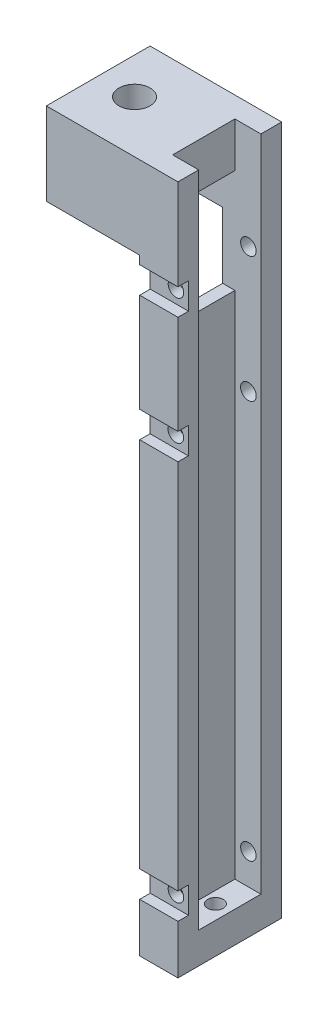
SolidWorks part; units mm, degrees
material "Delrin 2700 NC010, Low Viscosity Acetal Copolymer (SS)"
ref_plane "Front Plane" through (0, 0, 0) normal (0, 0, 1) x (1, 0, 0)
ref_plane "Top Plane" through (0, 0, 0) normal (0, 1, 0) x (1, 0, 0)
ref_plane "Right Plane" through (0, 0, 0) normal (1, 0, 0) x (0, 0, -1)
sketch "Sketch1" plane through (0, 0, 0) normal (0, 0, 1) x (1, 0, 0)
  line L0 (-4, 0) -> (-0.82, 0)
  line L1 (-0.82, 0) -> (-0.82, 21.5)
  line L2 (-6.32, 21.5) -> (-6.32, 17.5)
  line L3 (-4, 17.5) -> (-4, 0)
  line L4 (-6.32, 17.5) -> (-4, 17.5)
  line L5 (-0.82, 21.5) -> (-6.32, 21.5)
  dimension "D1" = 3.18
  dimension "D2" = 5.5
  dimension "D3" = 4
extrude "Boss-Extrude2" add sketch "Sketch1" along normal blind 10
sketch "Sketch2" plane through (-0.82, 0, 0) normal (1, 0, 0) x (0, 0, -1)
  line L1 (-10, 0) -> (0, 0) construction
  line L3 (-8, 0) -> (-2, 0)
  line L4 (-2, 0) -> (-2, 21.5)
  line L5 (-10, 21.5) -> (0, 21.5) construction
  line L6 (-2, 21.5) -> (-8, 21.5)
  line L7 (-8, 21.5) -> (-8, 0)
extrude "Cut-Extrude1" cut sketch "Sketch2" against normal blind 2
sketch "Sketch18" plane through (-6.32, 0, 0) normal (-1, 0, 0) x (0, 0, 1)
  line L0 (0, 21.5) -> (0, 17.5)
  line L1 (0, 21.5) -> (10, 21.5)
  line L2 (10, 21.5) -> (10, 17.5)
  line L3 (10, 17.5) -> (0, 17.5)
extrude "Cut-Extrude6" cut sketch "Sketch18" against normal blind 2.32
sketch "Sketch19" plane through (0, 21.5, 0) normal (0, 1, 0) x (1, 0, 0)
  line L0 (-0.82, -10) -> (-4, -10)
  line L1 (-4, -10) -> (-4, 0)
  line L2 (-4, 0) -> (-0.82, 0)
  line L3 (-0.82, 0) -> (-0.82, -2)
  line L4 (-0.82, -2) -> (-2.82, -2)
  line L5 (-2.82, -2) -> (-2.82, -8)
  line L6 (-2.82, -8) -> (-0.82, -8)
  line L7 (-0.82, -8) -> (-0.82, -10)
extrude "Boss-Extrude4" add sketch "Sketch19" along normal blind 35.965
sketch "Sketch20" plane through (-4, 0, 0) normal (-1, 0, 0) x (0, 0, 1)
  line L0 (10, 57.465) -> (10, 53.147)
  line L1 (10, 57.465) -> (10, 0) construction
  line L2 (10, 53.147) -> (0, 53.147)
  line L3 (0, 57.465) -> (0, 0) construction
  line L4 (0, 53.147) -> (0, 57.465)
  line L5 (0, 57.465) -> (10, 57.465)
  dimension "D1" = 4.318
extrude "Boss-Extrude5" add sketch "Sketch20" along normal blind 9
ref_plane "Plane1" through (0, 0, 5) normal (0, 0, 1) x (1, 0, 0)
sketch "Sketch21" plane through (-0.82, 0, 0) normal (1, 0, 0) x (0, 0, -1)
  line L0 (-10, 0) -> (-8, 0)
  line L1 (-8, 0) -> (-8, 57.465)
  line L2 (-8, 57.465) -> (-10, 57.465)
  line L3 (-10, 57.465) -> (-10, 0)
  line L4 (-2, 0) -> (0, 0)
  line L5 (0, 0) -> (0, 57.465)
  line L6 (0, 57.465) -> (-2, 57.465)
  line L7 (-2, 57.465) -> (-2, 0)
extrude "Boss-Extrude6" add sketch "Sketch21" along normal blind 0.889
sketch "Sketch22" plane through (0, 0, 0) normal (0, -1, 0) x (1, 0, 0)
  line L0 (-4, 10) -> (0.069, 10)
  line L1 (0.069, 10) -> (0.069, 8)
  line L2 (0.069, 8) -> (-2.82, 8)
  line L3 (-2.82, 8) -> (-2.82, 2)
  line L4 (-2.82, 2) -> (0.069, 2)
  line L5 (0.069, 2) -> (0.069, 0)
  line L6 (0.069, 0) -> (-4, 0)
  line L7 (-4, 0) -> (-4, 10)
extrude "Boss-Extrude7" add sketch "Sketch22" along normal blind 9.02
sketch "Sketch23" plane through (0, 0, 10) normal (0, 0, 1) x (1, 0, 0)
  line L0 (0.069, -3.02) -> (0.069, -4.29)
  line L1 (0.069, -1.75) -> (-4, -1.75)
  line L2 (0.069, 57.465) -> (0.069, -9.02) construction
  line L3 (0.069, -3.02) -> (0.069, -1.75)
  line L4 (0.069, -3.02) -> (0.069, -9.02) construction
  line L5 (-4, 53.147) -> (-4, -9.02) construction
  line L6 (-4, -1.75) -> (-4, -4.29)
  line L7 (-4, -4.29) -> (0.069, -4.29)
  line L8 (-4, 47.4267) -> (-4, 48.6967)
  line L9 (-4, 47.4267) -> (-4, 46.1567)
  line L10 (-4, 48.6967) -> (0.069, 48.6967)
  line L11 (0.069, 48.6967) -> (0.069, 46.1567)
  line L12 (0.069, 46.1567) -> (-4, 46.1567)
  dimension "D1" = 1.27
  dimension "D2" = 1.27
  dimension "D3" = 1.27
  dimension "D4" = 1.27
  dimension "D5" = 6
extrude "Cut-Extrude7" cut sketch "Sketch23" against normal blind 1.016
sketch "Sketch24" plane through (0, 0, 10) normal (0, 0, 1) x (1, 0, 0)
  line L0 (0.069, 34.085) -> (0.069, 36.625)
  line L1 (0.069, 46.1567) -> (0.069, -1.75) construction
  line L2 (-4, 46.1567) -> (-4, -1.75) construction
  line L5 (0.069, 36.625) -> (-4, 36.625)
  line L6 (-4, 36.625) -> (-4, 34.085)
  line L7 (-4, 34.085) -> (0.069, 34.085)
extrude "Cut-Extrude8" cut sketch "Sketch24" against normal blind 1
extrude "Cut-Extrude9" cut sketch "Sketch25" against normal through all
sketch "Sketch25" plane through (35.0631, -23.6783, 8.984) normal (0, 0, 1) x (1, 0, 0)
  circle A0 centre (-36.5816, 71.105) radius 0.7556
  circle A1 centre (-36.5816, 59.0333) radius 0.7556
  circle A2 centre (-36.5816, 25.3583) radius 0.7557
extrude "Cut-Extrude14" cut sketch "Sketch30" against normal through all
sketch "Sketch30" plane through (35.0631, -23.6783, 9) normal (0, 0, 1) x (1, 0, 0)
  circle A0 centre (-36.5816, 59.0333) radius 0.7556
sketch "Sketch34" plane through (0, 57.465, 0) normal (0, 1, 0) x (1, 0, 0)
  line L2 (-2.3749, -5) -> (2.3749, -5) construction
  circle A0 centre (-9.5, -5) radius 1.5
  dimension "D1" = 3
extrude "Cut-Extrude18" cut sketch "Sketch34" against normal blind 10
sketch "Sketch35" plane through (0, 0, 8.984) normal (0, 0, 1) x (1, 0, 0)
  line L0 (-1.5185, 35.355) -> (-1.5185, 46.1567) construction
  line L1 (-4, 46.1567) -> (0.069, 46.1567) construction
  line L2 (-1.5185, 35.355) -> (-1.5185, -1.75) construction
  line L3 (0.069, -1.75) -> (-4, -1.75) construction
  line L4 (-1.5185, 46.1567) -> (-1.5185, 47.4567) construction
  line L5 (-1.5185, -1.75) -> (-1.5185, -3.05) construction
  circle A0 centre (-1.5185, 47.4567) radius 0.75
  circle A1 centre (-1.5185, -3.05) radius 0.75
  dimension "D2" = 1.3
  dimension "D1" = 1.3
extrude "Cut-Extrude19" cut sketch "Sketch35" against normal through all
sketch "Sketch36" plane through (-2.82, 0, 0) normal (1, 0, 0) x (0, 0, -1)
  line L0 (-8, 53.147) -> (-2, 53.147) construction
  line L1 (-8, 57.465) -> (-8, -9.02) construction
  line L2 (0, 53.147) -> (-10, 53.147) construction
  line L3 (-2, 57.465) -> (-2, -9.02) construction
  line L4 (-2, -9.02) -> (-2, 57.465) construction
  line L5 (-8, 53.147) -> (-8, 43.147) construction
  line L6 (-8, -9.02) -> (-8, 57.465) construction
  line L7 (-8, 53.147) -> (-2, 53.147)
  line L8 (-8, 53.147) -> (-8, 43.147)
  line L9 (-8, 43.147) -> (-2, 43.147)
  line L10 (-2, 43.147) -> (-2, 53.147)
  dimension "D1" = 10
extrude "Cut-Extrude20" cut sketch "Sketch36" against normal blind 10
sketch "Sketch37" plane through (0, 53.147, 0) normal (0, -1, 0) x (1, 0, 0)
  line L0 (-13, 10) -> (-4, 10)
  line L1 (-4, 10) -> (-4, 8)
  line L2 (-4, 8) -> (-13, 8)
  line L3 (-13, 0) -> (-13, 10) construction
  line L4 (-13, 8) -> (-13, 10)
  line L5 (-4, 2) -> (-4, 0)
  line L6 (-4, 0) -> (-13, 0)
  line L7 (-4, 2) -> (-13, 2)
  line L8 (-13, 2) -> (-13, 0)
extrude "Boss-Extrude8" add sketch "Sketch37" along normal blind 3.65
sketch "Sketch38" plane through (0, -9.02, 0) normal (0, -1, 0) x (1, 0, 0)
  line L0 (-4, 10) -> (0.069, 10)
  line L1 (0.069, 10) -> (0.069, 0)
  line L2 (0.069, 0) -> (-4, 0)
  line L3 (-4, 0) -> (-4, 10)
extrude "Boss-Extrude9" add sketch "Sketch38" against normal blind 3
sketch "Sketch39" plane through (0, -9.02, 0) normal (0, -1, 0) x (1, 0, 0)
  line L0 (-4, 10) -> (-1.7, 10) construction
  line L4 (0.069, 10) -> (-4, 10) construction
  line L6 (-1.7, 10) -> (-1.7, 0) construction
  line L7 (-4, 0) -> (0.069, 0) construction
  circle A0 centre (-1.7, 5) radius 0.75
  dimension "D2" = 1.5
  dimension "D1" = 2.3
extrude "Cut-Extrude21" cut sketch "Sketch39" against normal blind 3
sketch "Sketch40" plane through (0, 57.465, 0) normal (0, 1, 0) x (1, 0, 0)
  line L0 (0.069, 0) -> (0.069, -10)
  line L1 (0.069, -10) -> (-0.312, -10)
  line L2 (-13, -10) -> (0.069, -10) construction
  line L3 (-0.312, -10) -> (-0.312, 0)
  line L4 (0.069, 0) -> (-13, 0) construction
  line L5 (-0.312, 0) -> (0.069, 0)
  dimension "D1" = 0.381
extrude "Cut-Extrude22" cut sketch "Sketch40" against normal through all
